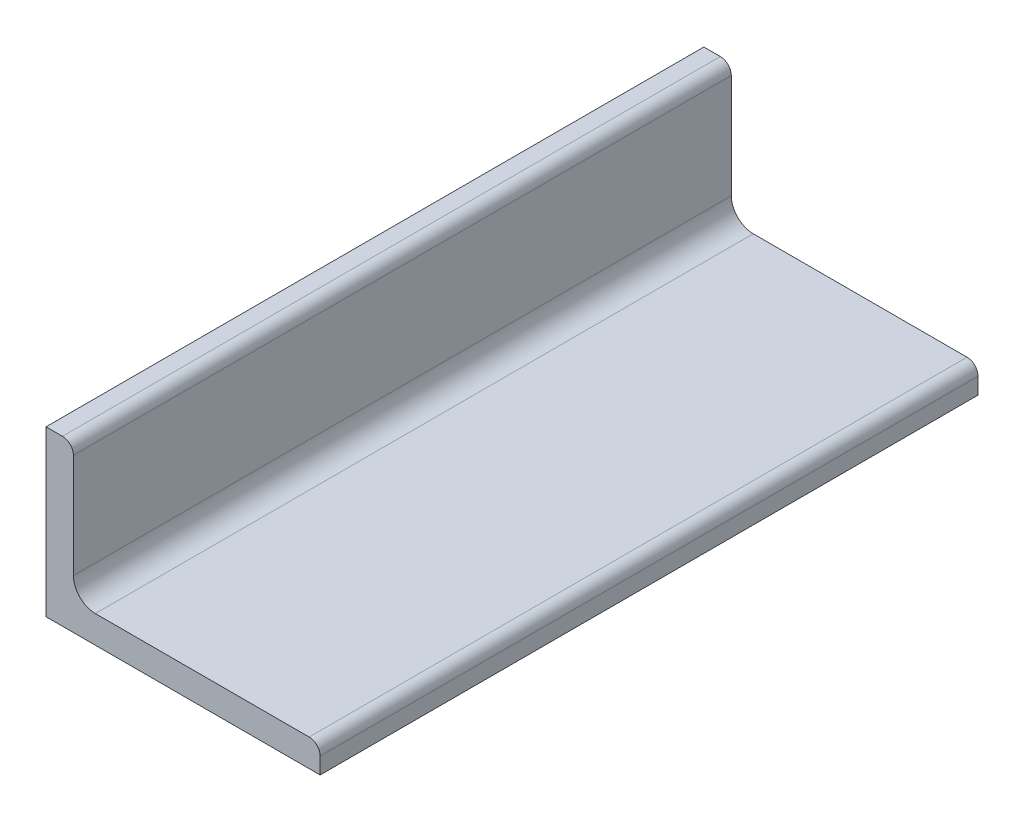
SolidWorks part; units mm, degrees
other "Markup1"
sketch "Sketch8" plane through (150, 90, -130) normal (0.0069, 0.5696, -0.8219) x (-1, -0.0001, -0.0085)
ref_plane "Front Plane" through (0, 0, 0) normal (0, 0, 1) x (1, 0, 0)
ref_plane "Top Plane" through (0, 0, 0) normal (0, 1, 0) x (1, 0, 0)
ref_plane "Right Plane" through (0, 0, 0) normal (1, 0, 0) x (0, 0, -1)
sketch3d "3DSketch1"
  line L0 (0, 0, -180) -> (0, 0, 180)
  point P4 (0, 0, 0)
  dimension "D1" = 360
other "Ea RSA40X40X5(1)"
ref_plane "Plane1" through (0, 0, -180) normal (0, 0, 1) x (1, 0, 0)
sketch "Sketch1" plane through (0, 0, -180) normal (0, 0, 1) x (1, 0, 0)
  line L0 (0, 90) -> (0, 0)
  line L1 (0, 90) -> (15, 90) construction
  line L2 (15, 84) -> (15, 27)
  line L3 (27, 15) -> (144, 15)
  line L4 (150, 15) -> (150, 0) construction
  line L5 (150, 0) -> (0, 0)
  line L6 (150, 9) -> (150, 0)
  line L7 (0, 90) -> (9, 90)
  arc A0 (9, 90) -> (15, 84) centre (9, 84) cw
  arc A1 (150, 9) -> (144, 15) centre (144, 9) ccw
  arc A2 (27, 15) -> (15, 27) centre (27, 27) cw
  point P8 (15, 90)
  point P16 (150, 15)
  point P17 (0, 45)
  point P18 (75, 0)
  point P19 (0, 0)
  dimension "Radius_1" = 12
  dimension "radius_2" = 6
  dimension "V_leg" = 90
  dimension "H_leg" = 150
  dimension "thickness" = 15
sketch "Sketch5" plane through (0, 15, 0) normal (0, 1, 0) x (1, 0, 0)
  line L0 (105, 180) -> (105, -180) construction
  line L1 (150, 180) -> (0, 180) construction
  line L2 (144, -180) -> (27, -180) construction
  line L3 (150, -180) -> (150, 180) construction
  dimension "D1" = 45
